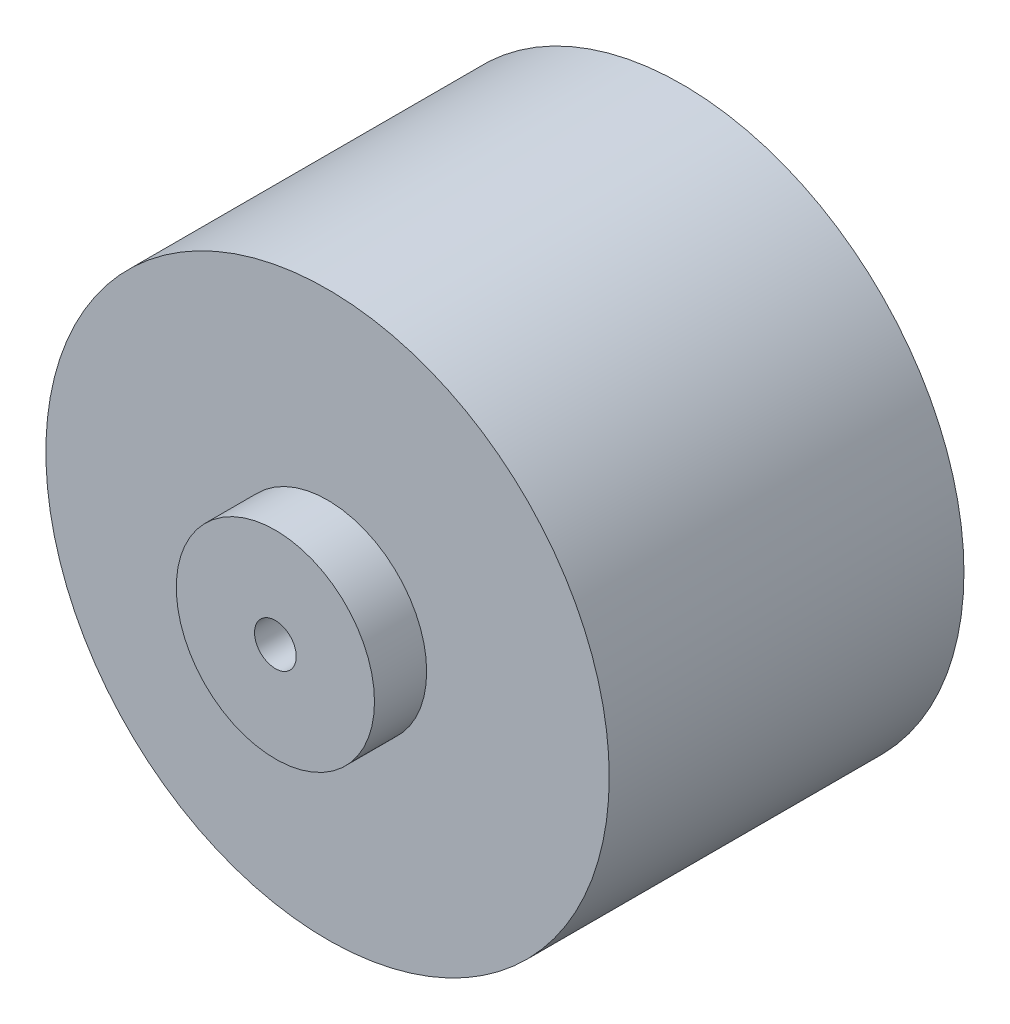
SolidWorks part; units mm, degrees
ref_plane "Front Plane" through (0, 0, 0) normal (0, 0, 1) x (1, 0, 0)
ref_plane "Top Plane" through (0, 0, 0) normal (0, 1, 0) x (1, 0, 0)
ref_plane "Right Plane" through (0, 0, 0) normal (1, 0, 0) x (0, 0, -1)
sketch "Sketch1" plane through (0, 0, 0) normal (0, 0, 1) x (1, 0, 0)
  circle A0 centre (0, 0) radius 27
extrude "Boss-Extrude1" add sketch "Sketch1" along normal blind 34
sketch "Sketch2" plane through (0, 0, 34) normal (0, 0, 1) x (1, 0, 0)
  circle A0 centre (0, 0) radius 9.5
extrude "Boss-Extrude2" add sketch "Sketch2" along normal blind 5
sketch "Sketch3" plane through (0, 0, 39) normal (0, 0, 1) x (1, 0, 0)
  circle A0 centre (0, 0) radius 2
extrude "Cut-Extrude1" cut sketch "Sketch3" against normal blind 30
